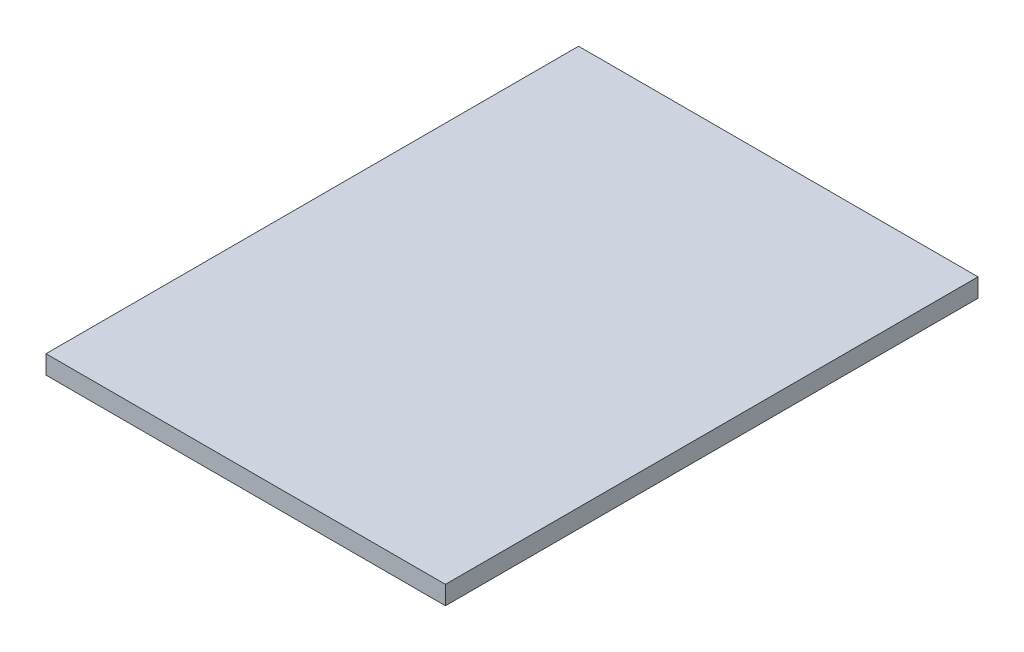
SolidWorks part; units mm, degrees
ref_plane "Front Plane" through (0, 0, 0) normal (0, 0, 1) x (1, 0, 0)
ref_plane "Top Plane" through (0, 0, 0) normal (0, 1, 0) x (1, 0, 0)
ref_plane "Right Plane" through (0, 0, 0) normal (1, 0, 0) x (0, 0, -1)
sketch "Sketch2" plane through (0, 0, 0) normal (0, 1, 0) x (1, 0, 0)
  line L1 (-32.25, 43) -> (32.25, 43)
  line L2 (-32.25, 43) -> (-32.25, -43)
  line L3 (-32.25, -43) -> (32.25, -43)
  line L4 (32.25, 43) -> (32.25, -43)
  line L5 (-32.25, 43) -> (32.25, -43) construction
  line L6 (-32.25, -43) -> (32.25, 43) construction
  point P0 (0, 0)
  dimension "D1" = 86
extrude "Boss-Extrude3" add sketch "Sketch2" along normal blind 3
